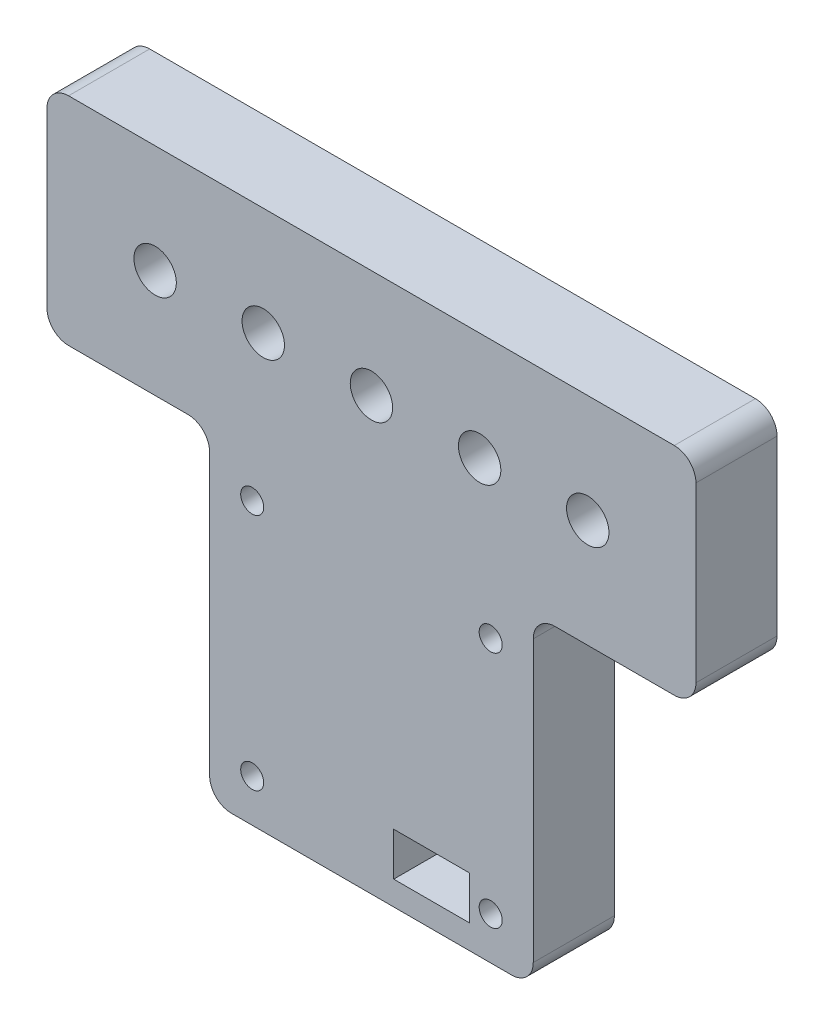
SolidWorks part; units mm, degrees
ref_plane "Front Plane" through (0, 0, 0) normal (1, 0, 0) x (0, 1, 0)
ref_plane "Top Plane" through (0, 0, 0) normal (0, 0, 1) x (0, 1, 0)
ref_plane "Right Plane" through (0, 0, 0) normal (0, 1, 0) x (-1, 0, 0)
sketch "Sketch1" plane through (0, 0, 0) normal (0, 0, 1) x (0, 1, 0)
  line L1 (-14, -14) -> (14, -14) construction
  line L2 (-14, -14) -> (-14, 14) construction
  line L3 (-14, 14) -> (14, 14) construction
  line L4 (14, -14) -> (14, 14) construction
  line L5 (-14, -14) -> (14, 14) construction
  line L6 (-14, 14) -> (14, -14) construction
  line L7 (-19, -19) -> (19, -19)
  line L8 (-19, -19) -> (-19, 19)
  line L9 (-19, 19) -> (19, 19)
  line L10 (19, -19) -> (19, 19)
  line L11 (-19, -19) -> (19, 19) construction
  line L12 (-19, 19) -> (19, -19) construction
  point P0 (0, 0)
  point P7 (0, 0)
  dimension "D1" = 28
  dimension "D2" = 28
  dimension "D3" = 38
  dimension "D4" = 38
extrude "Boss-Extrude1" add sketch "Sketch1" along normal blind 9.525
sketch "Sketch2" plane through (0, 0, 9.525) normal (0, 0, 1) x (1, 0, 0)
  point P0 (-14, -14)
  point P2 (14, -14)
  point P4 (14, 14)
  point P6 (-14, 14)
hole_wizard "#36 (0.1065) Diameter Hole2" positions "Sketch2" profile "Sketch4" hole size "#36" standard "ANSI Inch" end condition through all
sketch "Sketch4" plane through (-14, -14, 9.525) normal (1, 0, 0) x (0, -1, 0)
  line L0 (0, 0) -> (0, 9.525)
  line L1 (0, 9.525) -> (1.3525, 9.525)
  line L2 (1.3525, 9.525) -> (1.3525, 0)
  line L5 (1.3525, 0) -> (0, 0)
  line L11 (0, -6.35) -> (0, 107.95) construction
  dimension "Thru Hole Dia." = 2.7051
  dimension "Thru Hole Depth" = 9.525
sketch "Sketch7" plane through (0, 0, 0) normal (0, 0, -1) x (1, 0, 0)
  line L1 (2.615, 11.09) -> (11.505, 11.09)
  line L2 (2.615, 11.09) -> (2.615, 16.17)
  line L3 (2.615, 16.17) -> (11.505, 16.17)
  line L4 (11.505, 11.09) -> (11.505, 16.17)
  line L5 (2.615, 11.09) -> (11.505, 16.17) construction
  line L6 (2.615, 16.17) -> (11.505, 11.09) construction
  circle A0 centre (14, 14) radius 1.3525 construction
  point P0 (7.06, 13.63)
  dimension "D1" = 8.89
  dimension "D2" = 5.08
  dimension "D3" = 0.37
  dimension "D4" = 6.94
extrude "Cut-Extrude1" cut sketch "Sketch7" against normal through all
sketch "Sketch8" plane through (0, 19, 0) normal (0, 1, 0) x (-1, 0, 0)
  line L1 (38.1, 9.525) -> (-38.1, 9.525)
  line L2 (38.1, 9.525) -> (38.1, 0)
  line L3 (38.1, 0) -> (-38.1, 0)
  line L4 (-38.1, 9.525) -> (-38.1, 0)
  point P4 (0, 0)
  point P8 (0, 0)
  dimension "D1" = 76.2
extrude "Boss-Extrude2" add sketch "Sketch8" along normal blind 25.4
sketch "Sketch9" plane through (0, 0, 0) normal (0, 0, -1) x (1, 0, 0)
  line L0 (-19, -19) -> (-38.1, -19) construction
  line L1 (-38.1, -44.4) -> (-38.1, -19) construction
  point P0 (-25.4, -31.7)
  point P6 (0, 0)
  point P7 (0, 0)
  point P8 (-12.7, -31.7)
  point P9 (0, -31.7)
  point P10 (12.7, -31.7)
  point P11 (25.4, -31.7)
  point P12 (0, 0)
  point P13 (0, 0)
  point P14 (0, 0)
  dimension "D1" = 12.7
  dimension "D2" = 12.7
  dimension "D4" = 12.7
  dimension "D3" = 5
hole_wizard "#9 (0.196) Diameter Hole1" positions "Sketch9" profile "Sketch10" hole size "#9" standard "ANSI Inch" end condition through all
sketch "Sketch10" plane through (-25.4, 31.7, 0) normal (1, 0, 0) x (0, 1, 0)
  line L0 (0, 0) -> (0, 9.525)
  line L1 (0, 9.525) -> (2.4892, 9.525)
  line L2 (2.4892, 9.525) -> (2.4892, 0)
  line L5 (2.4892, 0) -> (0, 0)
  line L11 (0, -6.35) -> (0, 107.95) construction
  dimension "Thru Hole Dia." = 4.9784
  dimension "Thru Hole Depth" = 9.525
fillet "Fillet1" radius 2.54 8 edges at (-38.1, 44.4, 4.7625) (38.1, 44.4, 4.7625) (38.1, 19, 4.7625) (19, 19, 4.7625) (19, -19, 4.7625) (-19, -19, 4.7625) (-19, 19, 4.7625) (-38.1, 19, 4.7625)
